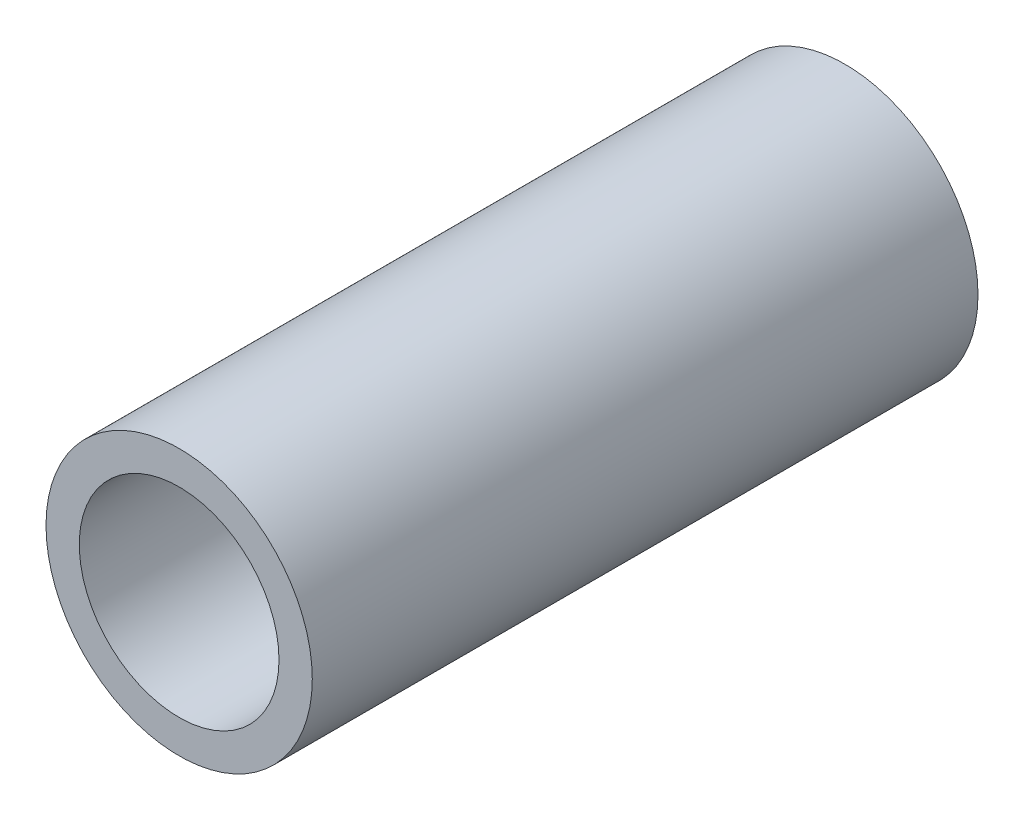
SolidWorks part; units mm, degrees
ref_plane "Alzado" through (0, 0, 0) normal (0, 0, 1) x (1, 0, 0)
ref_plane "Planta" through (0, 0, 0) normal (0, 1, 0) x (1, 0, 0)
ref_plane "Vista lateral" through (0, 0, 0) normal (1, 0, 0) x (0, 0, -1)
sketch "Croquis1" plane through (0, 0, 0) normal (0, 0, 1) x (1, 0, 0)
  circle A0 centre (0, 0) radius 12.7
  dimension "D1" = 25.4
extrude "Extruir-Lámina1" add sketch "Croquis1" along normal mid plane 63.5 thin thin type one direction reverse wall 3.175
